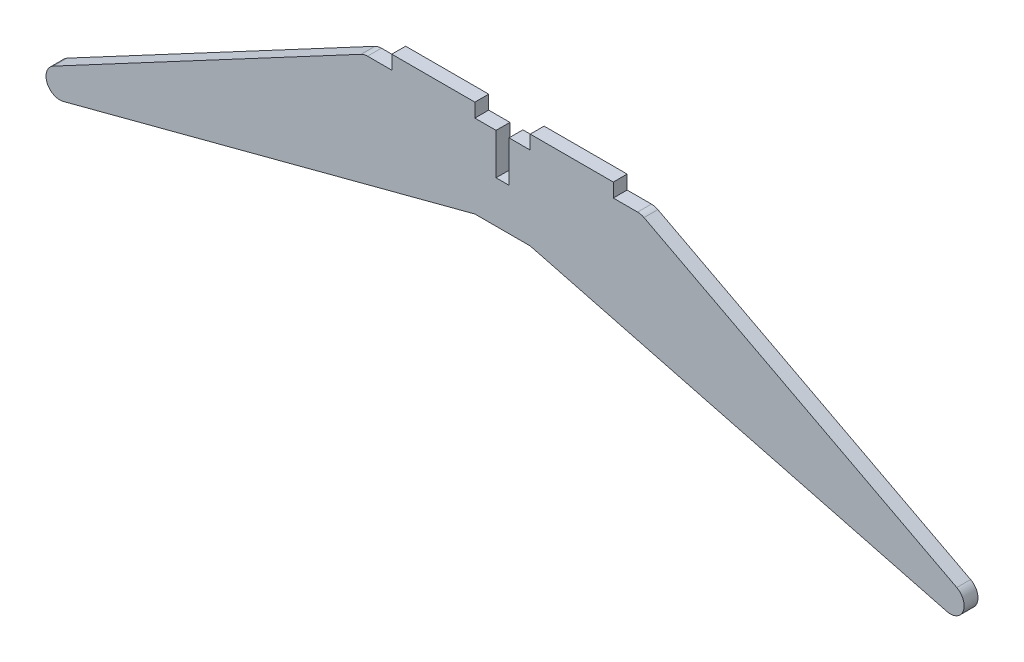
SolidWorks part; units mm, degrees
material "Teak"
ref_plane "Front Plane" through (0, 0, 0) normal (0, 0, 1) x (1, 0, 0)
ref_plane "Top Plane" through (0, 0, 0) normal (0, 1, 0) x (1, 0, 0)
ref_plane "Right Plane" through (0, 0, 0) normal (1, 0, 0) x (0, 0, -1)
sketch "Sketch1" plane through (0, 0, 0) normal (0, 0, 1) x (1, 0, 0)
  line L0 (25.4, 0) -> (30.968, 0)
  line L1 (1.4859, 0) -> (6.35, 0)
  line L2 (1.4859, 0) -> (1.4859, -9.4234)
  line L3 (-1.4859, 0) -> (-1.4859, -9.4234)
  line L4 (-25.4, 0) -> (-30.9562, 0)
  line L5 (-32.4504, -0.3735) -> (-103.0239, -38.0127)
  line L6 (-100.7218, -43.8847) -> (-6.35, -19.05)
  line L7 (-6.35, -19.05) -> (6.35, -19.05)
  line L8 (6.35, -19.05) -> (101.8924, -43.8589)
  line L9 (104.1649, -37.9739) -> (32.4425, -0.3632)
  line L10 (1.4859, -9.4234) -> (-1.4859, -9.4234)
  line L11 (-1.4859, 0) -> (-6.35, 0)
  line L12 (-6.35, 3.175) -> (-25.4, 3.175)
  line L13 (6.35, 3.175) -> (25.4, 3.175)
  line L14 (-25.4, 0) -> (-25.4, 3.175)
  line L15 (-6.35, 3.175) -> (-6.35, 0)
  line L16 (6.35, 0) -> (6.35, 3.175)
  line L17 (25.4, 3.175) -> (25.4, 0)
  arc A0 (-30.9562, 0) -> (-32.4504, -0.3735) centre (-30.9562, -3.175) ccw
  arc A1 (-103.0239, -38.0127) -> (-100.7218, -43.8847) centre (-101.5298, -40.8142) ccw
  arc A2 (101.8924, -43.8589) -> (104.1649, -37.9739) centre (102.6904, -40.7858) ccw
  arc A3 (32.4425, -0.3632) -> (30.968, 0) centre (30.968, -3.175) ccw
  point P25 (-6.35, 0)
  point P30 (6.35, 0)
extrude "Boss-Extrude1" add sketch "Sketch1" along normal blind 3.175
